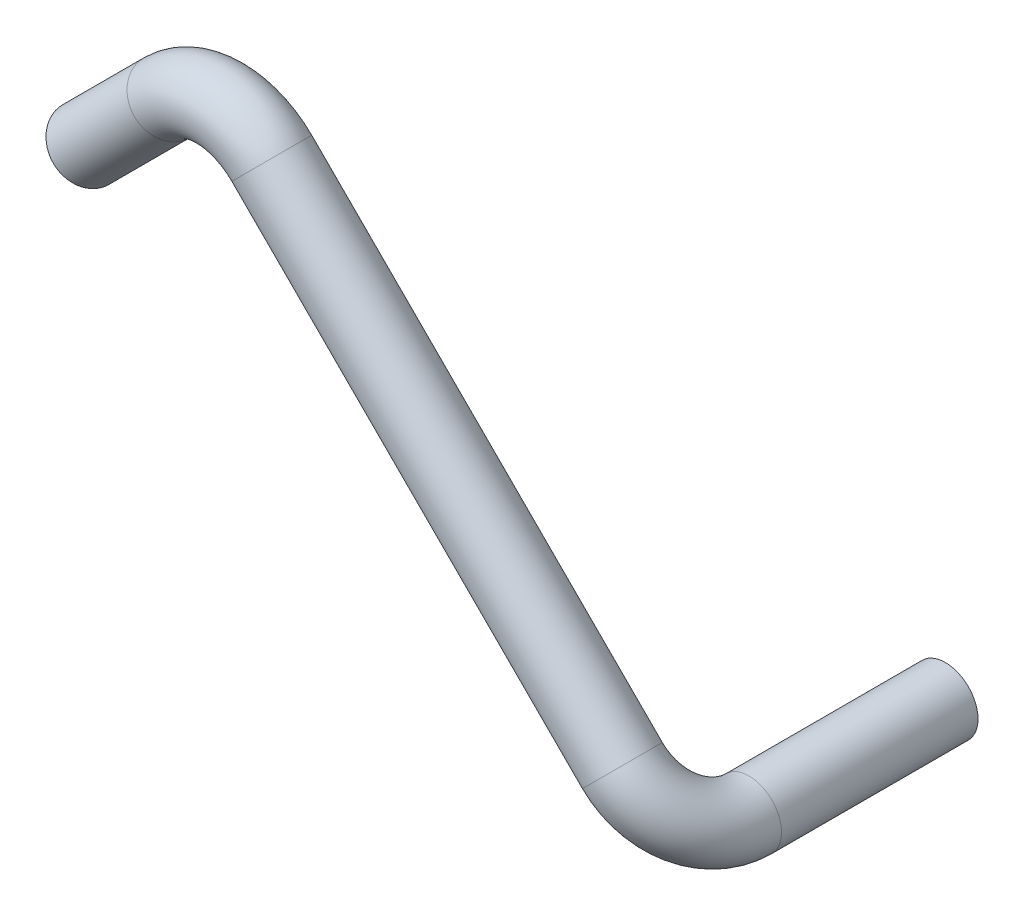
SolidWorks part; units mm, degrees
ref_plane "Front" through (0, 0, 0) normal (0, 0, 1) x (1, 0, 0)
ref_plane "Top" through (0, 0, 0) normal (0, 1, 0) x (1, 0, 0)
ref_plane "Side" through (0, 0, 0) normal (1, 0, 0) x (0, 0, -1)
sketch "PipeSketch" plane through (0, 0, 0) normal (0, 0, 1) x (1, 0, 0)
  circle A0 centre (0, 0) radius 16.764
  circle A1 centre (0, 0) radius 13.3858
  dimension "OuterDiameter" = 33.528
  dimension "InnerDiameter" = 26.7716
extrude "Extrusion" add sketch "PipeSketch" along normal blind 95
sketch "FilterSketch" plane through (0, 0, 0) normal (0, 0, 1) x (1, 0, 0)
  circle A0 centre (0, 0) radius 12.7 construction
  dimension "NominalDiameter" = 25.4
sketch "草图3" plane through (0, 0, 95) normal (0, 0, 1) x (1, 0, 0)
  circle A0 centre (0, 0) radius 16.764 construction
  circle A1 centre (0, 0) radius 13.3858 construction
  circle A2 centre (0, 0) radius 16.764
  circle A3 centre (0, 0) radius 13.3858
extrude "凸台-拉伸2" add sketch "草图3" along normal blind 5.98
sketch "草图4" plane through (0, 0, 100.98) normal (0, 0, 1) x (1, 0, 0)
  line L0 (-26.9408, 26.9408) -> (-53.8815, 0) construction
  circle A0 centre (0, 0) radius 16.764 construction
  circle A1 centre (0, 0) radius 13.3858 construction
  circle A2 centre (0, 0) radius 16.764
  circle A3 centre (0, 0) radius 13.3858
revolve "旋转2" add sketch "草图4" angle 90 about L0
sketch "草图5" plane through (-26.9408, 26.9408, 0) normal (-0.7071, 0.7071, 0) x (0.7071, 0.7071, 0)
  circle A0 centre (0, -139.08) radius 13.3858 construction
  circle A1 centre (0, -139.08) radius 16.764 construction
  circle A2 centre (0, -139.08) radius 13.3858
  circle A3 centre (0, -139.08) radius 16.764
extrude "凸台-拉伸3" add sketch "草图5" along normal blind 254.9002
sketch "草图6" plane through (-207.1825, 207.1825, 0) normal (-0.7071, 0.7071, 0) x (0, 0, 1)
  line L0 (139.08, -38.1) -> (177.18, -38.1) construction
  circle A0 centre (139.08, 0) radius 16.764 construction
  circle A1 centre (139.08, 0) radius 13.3858 construction
  circle A2 centre (139.08, 0) radius 16.764
  circle A3 centre (139.08, 0) radius 13.3858
revolve "旋转3" add sketch "草图6" angle 90 about L0
sketch "草图7" plane through (-26.9408, -26.9408, 0) normal (-0.7071, -0.7071, 0) x (-0.7071, 0.7071, 0)
  circle A0 centre (331.1002, -139.08) radius 13.3858 construction
  circle A1 centre (331.1002, -139.08) radius 16.764 construction
  circle A2 centre (331.1002, -139.08) radius 13.3858
  circle A3 centre (331.1002, -139.08) radius 16.764
extrude "凸台-拉伸4" add sketch "草图7" along normal blind 58.9
